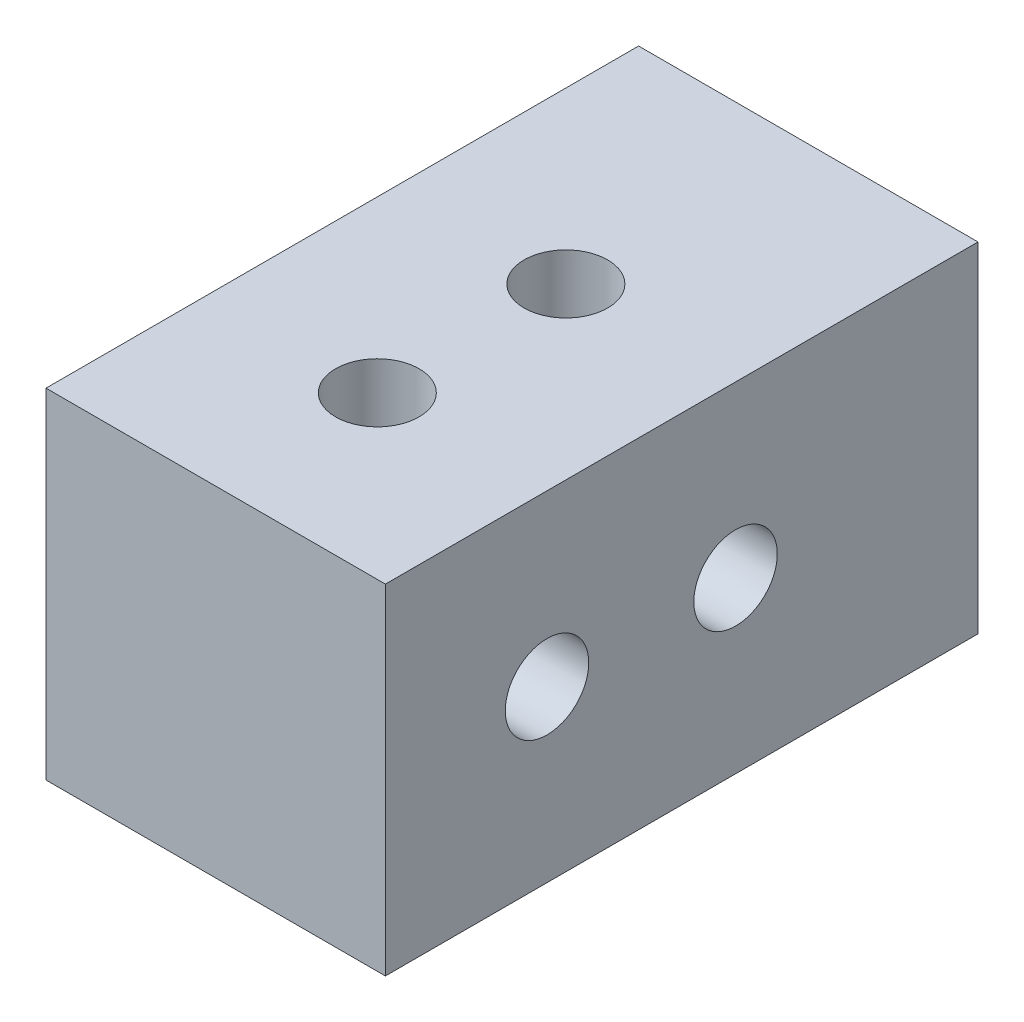
SolidWorks part; units mm, degrees
ref_plane "前视基准面" through (0, 0, 0) normal (0, 0, 1) x (1, 0, 0)
ref_plane "上视基准面" through (0, 0, 0) normal (0, 1, 0) x (1, 0, 0)
ref_plane "右视基准面" through (0, 0, 0) normal (1, 0, 0) x (0, 0, -1)
other "Configuration Table"
sketch "草图1" plane through (0, 0, 0) normal (0, 0, 1) x (1, 0, 0)
  line L1 (6.3, -6.3) -> (-6.3, -6.3)
  line L2 (6.3, -6.3) -> (6.3, 6.3)
  line L3 (6.3, 6.3) -> (-6.3, 6.3)
  line L4 (-6.3, -6.3) -> (-6.3, 6.3)
  line L5 (6.3, -6.3) -> (-6.3, 6.3) construction
  line L6 (6.3, 6.3) -> (-6.3, -6.3) construction
  point P0 (0, 0)
  dimension "D1" = 12.6
extrude "凸台-拉伸1" add sketch "草图1" along normal blind 22
sketch "草图2" plane through (0, 6.3, 0) normal (0, 1, 0) x (1, 0, 0)
  line L0 (6.3, 0) -> (-6.3, 0) construction
  line L1 (0, -9) -> (0, 0) construction
  circle A0 centre (0, -9) radius 1.55
  circle A1 centre (0, -16) radius 1.55
  dimension "D2" = 3.1
  dimension "D1" = 9
  dimension "D4" = 7
  dimension "D3" = 2
extrude "切除-拉伸1" cut sketch "草图2" against normal up to next
sketch "草图3" plane through (-6.3, 0, 0) normal (-1, 0, 0) x (0, 0, 1)
  line L0 (9, 0) -> (0, 0) construction
  circle A0 centre (9, 0) radius 1.55
  circle A1 centre (16, 0) radius 1.55
  dimension "D2" = 3.1
  dimension "D1" = 9
  dimension "D4" = 7
  dimension "D3" = 2
extrude "切除-拉伸2" cut sketch "草图3" against normal up to surface (12.6 mm away) up to face at (6.3, 0, 11)
